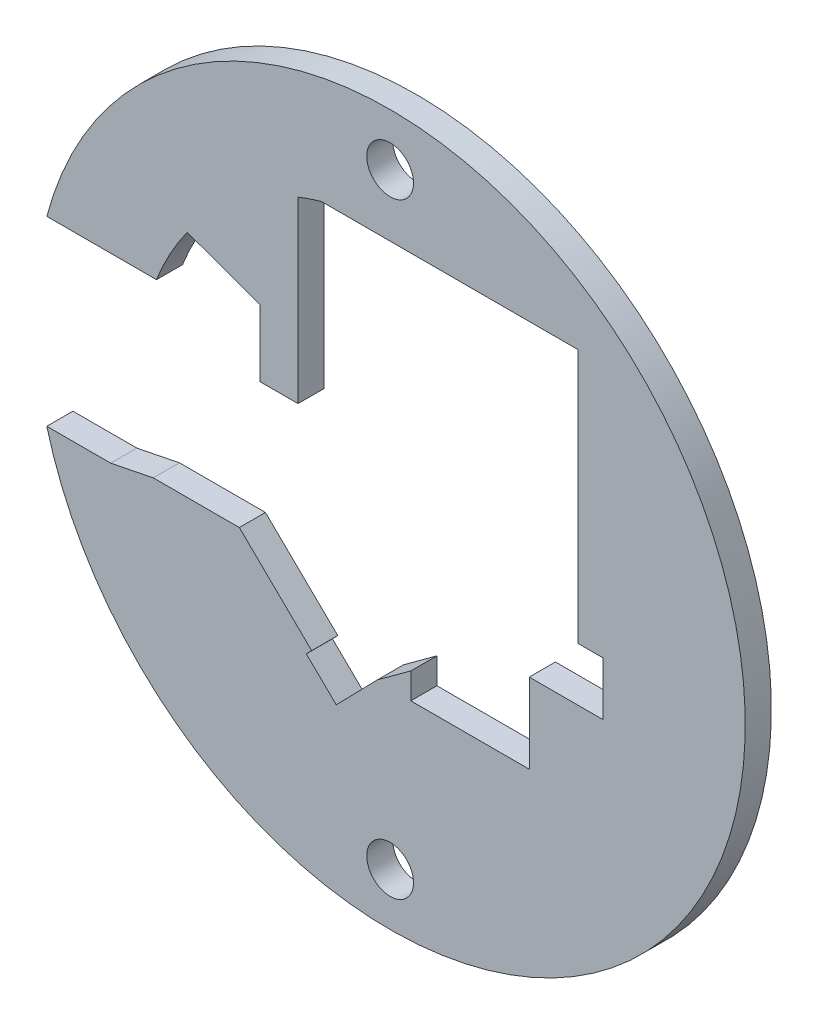
SolidWorks part; units mm, degrees
ref_plane "Front Plane" through (0, 0, 0) normal (0, 0, 1) x (1, 0, 0)
ref_plane "Top Plane" through (0, 0, 0) normal (0, 1, 0) x (1, 0, 0)
ref_plane "Right Plane" through (0, 0, 0) normal (1, 0, 0) x (0, 0, -1)
sketch "Sketch1" plane through (0, 0, 0) normal (0, 0, 1) x (1, 0, 0)
  line L1 (-14.9521, -2.9485) -> (-16.9841, -2.9485)
  line L2 (-16.9841, 2.9485) -> (-16.9841, 5.5245)
  line L3 (-14.9521, 2.9485) -> (-16.9841, 2.9485)
  line L4 (-16.9841, 5.5245) -> (-21.1739, 5.5245)
  line L5 (-16.9841, -2.9485) -> (-16.9841, -5.5245)
  line L6 (-16.9841, -5.5245) -> (-20.8712, -5.5245)
  line L7 (-15.24, 0) -> (-21.59, 0) construction
  line B0 (-15.24, 18.2372) -> (15.24, 18.2372)
  line B1 (11.43, 14.6558) -> (11.43, -0.8128)
  line B2 (0, 18.2372) -> (0, 0) construction
  line B3 (-5.6007, 14.1736) -> (-5.6007, -0.8128)
  line B4 (11.43, 14.6558) -> (-4.1791, 14.6558)
  line B5 (-5.6007, -0.8128) -> (11.43, -0.8128)
  line B6 (8.4582, -4.064) -> (12.9413, -4.064)
  line B7 (11.43, -0.8128) -> (12.9413, -0.8128)
  line B8 (12.9413, -0.8128) -> (12.9413, -4.064)
  line B9 (8.4582, -7.3406) -> (1.2573, -7.3406)
  line B10 (8.4582, -4.064) -> (8.4582, -7.3406)
  line B11 (-4.3942, -0.8128) -> (-4.3942, -4.064)
  line B12 (-4.3942, -4.064) -> (1.2573, -4.064)
  line B13 (1.2573, -4.064) -> (1.2573, -7.3406)
  line B14 (-0.7747, -8.8265) -> (-3.2737, -11.3919)
  line B15 (-0.7747, -8.8265) -> (-2.5941, -7.0541)
  line B16 (-2.5941, -7.0541) -> (-2.9176, -7.3862)
  line B17 (-2.9176, -7.3862) -> (-8.5123, -1.9362)
  line B18 (-8.5123, -1.9362) -> (-10.3645, -3.8375)
  line B19 (-10.3645, -3.8375) -> (-4.7697, -9.2875)
  line B20 (-4.7697, -9.2875) -> (-5.0932, -9.6195)
  line B21 (-5.0932, -9.6195) -> (-3.2737, -11.3919)
  line B22 (-12.3326, 18.2372) -> (-12.3326, 8.9535)
  line B23 (-7.9248, 18.2372) -> (-7.9248, 7.366) construction
  line B24 (-12.3326, 8.9535) -> (-7.9248, 7.366)
  line B25 (-5.6007, 3.302) -> (-7.9248, 3.302)
  line B26 (-7.9248, 3.302) -> (-7.9248, 7.366)
  line B27 (-14.3951, -5.0038) -> (-9.1672, -5.0038)
  line B28 (-0.7747, -8.8265) -> (1.2573, -7.3406)
  arc B29 (-3.302, 14.878) -> (3.302, 14.878) centre (0, 0) ccw
  circle B30 centre (0, -18.415) radius 1.4224
  circle B31 centre (0, 18.415) radius 1.4224
  circle B32 centre (0, 0) radius 21.59
  line B33 (1.2573, -8.9154) -> (8.4582, -8.9154)
  line B34 (1.2573, -7.3406) -> (1.2573, -8.9154)
  line B35 (8.4582, -7.3406) -> (8.4582, -8.9154)
  dimension "D1" = 2.032
  dimension "D2" = 11.049
sketch_block_instance "Block1-1"
sketch_block "Block1" parameters "D1"=3.81, "D2"=30.48, "D3"=3.5814, "D4"=9.6393, "D5"=19.05, "D6"=22.3012, "D7"=1.5113, "D8"=4.4831, "D9"=6.5278, "D10"=7.2009, "D11"=5.6515, "D12"=27.0637, "D13"=29.6291, "D14"=3.5814, "D15"=14.4653, "D16"=2.54, "D17"=2.6543, "D18"=10.3505, "D19"=9.2837, "D20"=10.8712, "D21"=7.3152, "D22"=14.9352, "D23"=23.241
extrude "Boss-Extrude1" add sketch "Sketch1" along normal blind 1.5875
sketch "Sketch2" plane through (0, 0, 1.5875) normal (0, 0, 1) x (1, 0, 0)
  line L0 (-14.3951, -5.0038) -> (-16.9841, -5.5245)
  line L2 (-16.9841, 5.5245) -> (-14.2034, 5.5245)
  line L3 (-14.3951, -5.0038) -> (-14.2034, 5.5245)
  line L4 (-16.9841, -5.5245) -> (-16.9841, 5.5245)
  arc A0 (-12.3326, 8.9535) -> (-14.9521, 2.9485) centre (0, 0) ccw construction
extrude "Cut-Extrude1" cut sketch "Sketch2" against normal through all
